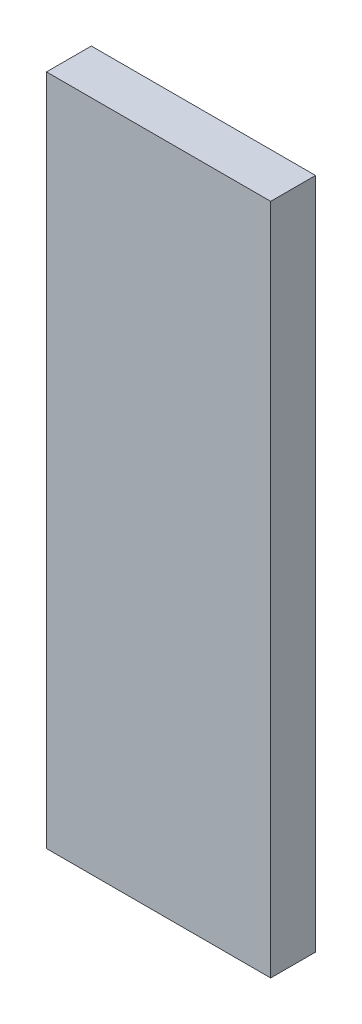
SolidWorks part; units mm, degrees
ref_plane "Front Plane" through (0, 0, 0) normal (0, 0, 1) x (1, 0, 0)
ref_plane "Top Plane" through (0, 0, 0) normal (0, 1, 0) x (1, 0, 0)
ref_plane "Right Plane" through (0, 0, 0) normal (1, 0, 0) x (0, 0, -1)
sketch "Sketch1" plane through (0, 0, 0) normal (0, 0, 1) x (1, 0, 0)
  line L1 (-142.789, 167.987) -> (-42.789, 167.987)
  line L2 (-142.789, 167.987) -> (-142.789, -132.013)
  line L3 (-142.789, -132.013) -> (-42.789, -132.013)
  line L4 (-42.789, 167.987) -> (-42.789, -132.013)
  dimension "D1" = 300
  dimension "D2" = 100
extrude "Boss-Extrude1" add sketch "Sketch1" along normal blind 20
